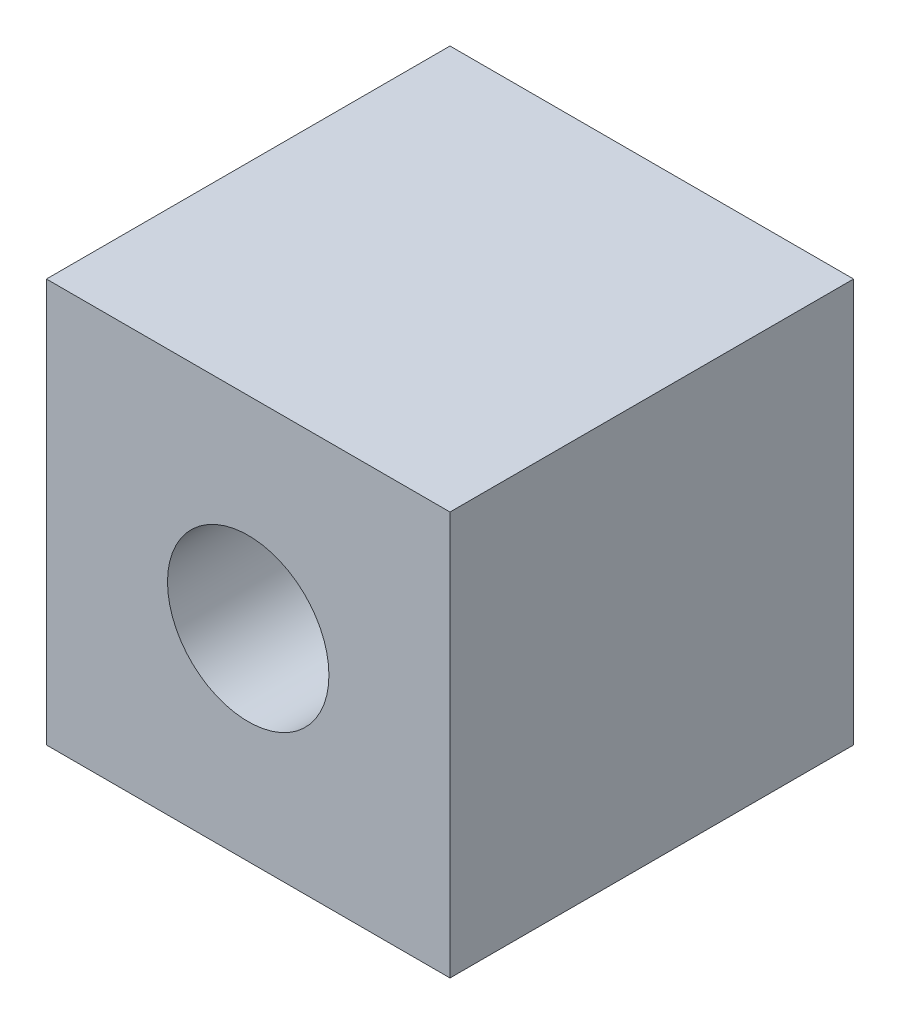
SolidWorks part; units mm, degrees
ref_plane "Front Plane" through (0, 0, 0) normal (0, 0, 1) x (1, 0, 0)
ref_plane "Top Plane" through (0, 0, 0) normal (0, 1, 0) x (1, 0, 0)
ref_plane "Right Plane" through (0, 0, 0) normal (1, 0, 0) x (0, 0, -1)
sketch "Sketch1" plane through (0, 0, 0) normal (0, 0, 1) x (1, 0, 0)
  line L1 (-25, 25) -> (25, 25)
  line L2 (-25, 25) -> (-25, -25)
  line L3 (-25, -25) -> (25, -25)
  line L4 (25, 25) -> (25, -25)
  line L5 (-25, 25) -> (25, -25) construction
  line L6 (-25, -25) -> (25, 25) construction
  point P0 (0, 0)
  dimension "D1" = 50
  dimension "D2" = 50
extrude "Boss-Extrude1" add sketch "Sketch1" along normal blind 50
sketch "Sketch2" plane through (0, 0, 50) normal (0, 0, 1) x (1, 0, 0)
  circle A0 centre (0, 0) radius 10
  dimension "D1" = 20
extrude "Cut-Extrude1" cut sketch "Sketch2" against normal blind 50
